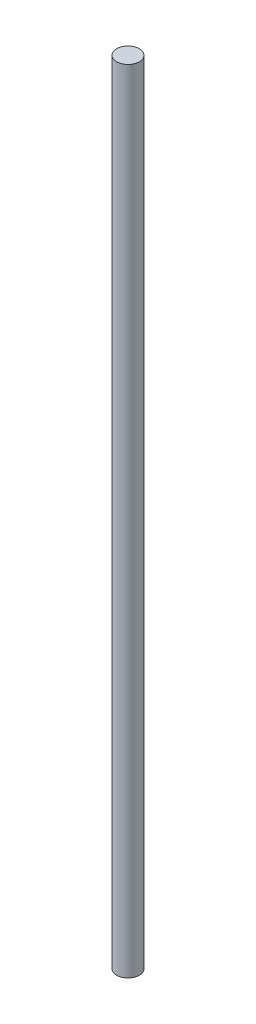
SolidWorks part; units mm, degrees
material "1060 合金"
ref_plane "前视基准面" through (0, 0, 0) normal (0, 0, 1) x (1, 0, 0)
ref_plane "上视基准面" through (0, 0, 0) normal (0, 1, 0) x (1, 0, 0)
ref_plane "右视基准面" through (0, 0, 0) normal (1, 0, 0) x (0, 0, -1)
other "Configuration Table"
sketch "草图1" plane through (0, 0, 0) normal (0, 1, 0) x (1, 0, 0)
  circle A0 centre (0, 0) radius 1
  dimension "D1" = 2
extrude "凸台-拉伸1" add sketch "草图1" along normal blind 70
